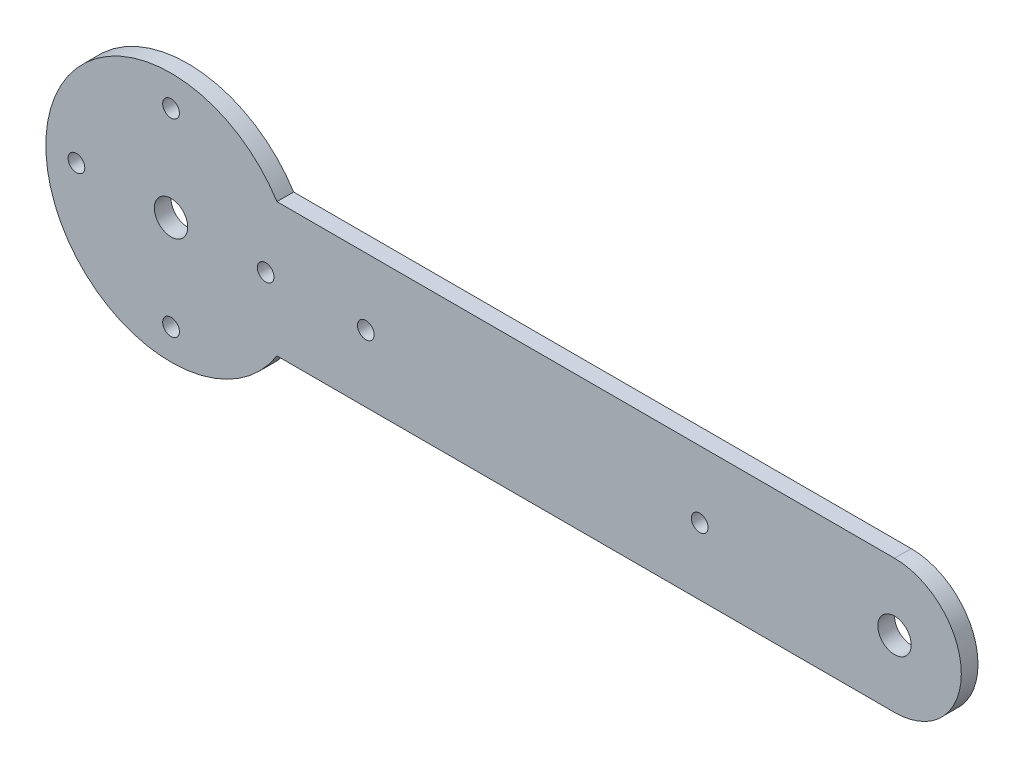
SolidWorks part; units mm, degrees
ref_plane "Plan de face" through (0, 0, 0) normal (0, 0, 1) x (1, 0, 0)
ref_plane "Plan de dessus" through (0, 0, 0) normal (0, 1, 0) x (1, 0, 0)
ref_plane "Plan de droite" through (0, 0, 0) normal (1, 0, 0) x (0, 0, -1)
sketch "Esquisse1" plane through (0, 0, 0) normal (0, 0, 1) x (1, 0, 0)
  line L0 (-79.2886, 0) -> (141.1723, 0) construction
  line L1 (0, 65.9449) -> (0, -87.2174) construction
  line L3 (-65, 12) -> (65, 12)
  line L5 (-65, -12) -> (65, -12)
  arc A0 (-65, 12) -> (-65, -12) centre (-65, 0) ccw
  arc A1 (65, 12) -> (65, -12) centre (65, 0) cw
  dimension "D2" = 12
  dimension "D1" = 130
extrude "Boss.-Extru.1" add sketch "Esquisse1" along normal blind 3
sketch "Esquisse2" plane through (0, 0, 3) normal (0, 0, 1) x (1, 0, 0)
  line L0 (0, 32.5631) -> (0, -50.0545) construction
  line L1 (0, 0) -> (-119.9738, 0) construction
  circle A0 centre (-65, 0) radius 3
  circle A1 centre (65, 0) radius 3
  arc A2 (-65, 12) -> (-65, -12) centre (-65, 0) ccw construction
  arc A3 (-65, 12) -> (-65, -12) centre (-65, 0) ccw construction
  circle A4 centre (-30, 0) radius 1.5
  circle A5 centre (30, 0) radius 1.5
  point P10 (-77, 0)
  dimension "D1" = 6
  dimension "D2" = 12
  dimension "D4" = 3
  dimension "D3" = 60
extrude "Enlèv. mat.-Extru.1" cut sketch "Esquisse2" against normal through all
sketch "Esquisse3" plane through (0, 0, 3) normal (0, 0, 1) x (1, 0, 0)
  circle A0 centre (-65, 0) radius 22.5
  circle A2 centre (-65, 0) radius 3
  dimension "D1" = 45
extrude "Boss.-Extru.2" add sketch "Esquisse3" against normal blind 3
sketch "Esquisse4" plane through (0, 0, 0) normal (0, 0, -1) x (-1, 0, 0)
  circle A0 centre (65, 0) radius 17 construction
  circle A1 centre (65, 17) radius 1.5
  circle A2 centre (82, 0) radius 1.5
  circle A3 centre (65, 0) radius 17 construction
  circle A4 centre (65, -17) radius 1.5
  circle A5 centre (65, 0) radius 17 construction
  circle A6 centre (48, 0) radius 1.5
  circle A7 centre (65, 0) radius 17 construction
  point P17 (65, 0)
  dimension "D1" = 17
  dimension "D2" = 3
  dimension "D3" = 4
extrude "Enlèv. mat.-Extru.2" cut sketch "Esquisse4" against normal through all
